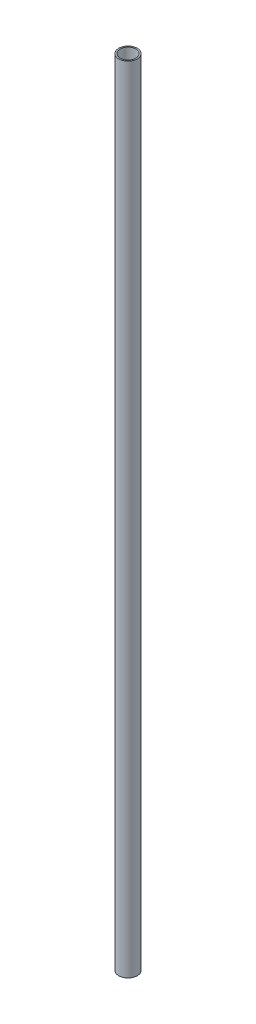
SolidWorks part; units mm, degrees
material "Thornel Mat VMA"
ref_plane "Front Plane" through (0, 0, 0) normal (0, 0, 1) x (1, 0, 0)
ref_plane "Top Plane" through (0, 0, 0) normal (0, 1, 0) x (1, 0, 0)
ref_plane "Right Plane" through (0, 0, 0) normal (1, 0, 0) x (0, 0, -1)
sketch "Sketch1" plane through (0, 0, 0) normal (0, 1, 0) x (1, 0, 0)
  circle A0 centre (0, 0) radius 6
  circle A1 centre (0, 0) radius 7
  dimension "D1" = 14
  dimension "D2" = 12
extrude "Boss-Extrude1" add sketch "Sketch1" along normal blind 600
